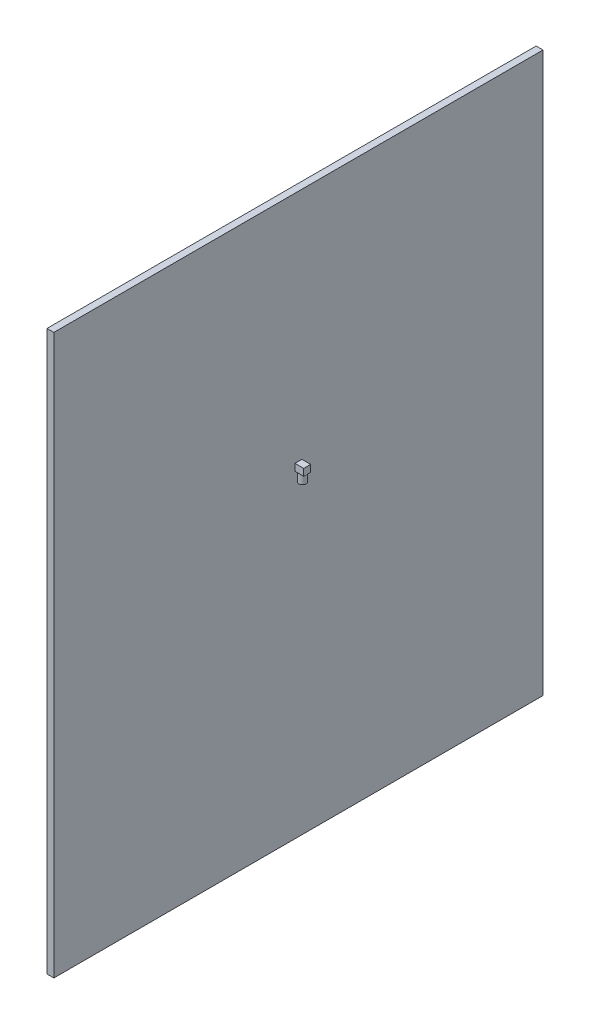
SolidWorks part; units mm, degrees
ref_plane "Front Plane" through (0, 0, 0) normal (0, 0, 1) x (1, 0, 0)
ref_plane "Top Plane" through (0, 0, 0) normal (0, 1, 0) x (1, 0, 0)
ref_plane "Right Plane" through (0, 0, 0) normal (1, 0, 0) x (0, 0, -1)
sketch "Sketch1" plane through (0, 0, 0) normal (1, 0, 0) x (0, 0, -1)
  line L1 (-355.6, 406.4) -> (355.6, 406.4)
  line L2 (-355.6, 406.4) -> (-355.6, -406.4)
  line L3 (-355.6, -406.4) -> (355.6, -406.4)
  line L4 (355.6, 406.4) -> (355.6, -406.4)
  line L5 (-355.6, 406.4) -> (355.6, -406.4) construction
  line L6 (-355.6, -406.4) -> (355.6, 406.4) construction
  point P0 (0, 0)
  dimension "D1" = 812.8
  dimension "D2" = 711.2
extrude "Boss-Extrude1" add sketch "Sketch1" along normal blind 10
sketch "Sketch2" plane through (10, 0, 0) normal (1, 0, 0) x (0, 0, -1)
  line L0 (0, 5.5) -> (0, -5.5) construction
  line L1 (-5, 66.3) -> (5, 66.3)
  line L2 (-5, 66.3) -> (-5, 56.3)
  line L3 (-5, 56.3) -> (5, 56.3)
  line L4 (5, 66.3) -> (5, 56.3)
  line L5 (-5, 66.3) -> (5, 56.3) construction
  line L6 (-5, 56.3) -> (5, 66.3) construction
  line L7 (-355.6, -406.4) -> (355.6, -406.4) construction
  point P0 (0, 61.3)
  dimension "D1" = 10
  dimension "D2" = 10
  dimension "D3" = 462.7
extrude "Boss-Extrude2" add sketch "Sketch2" along normal blind 12.7
sketch "Sketch4" plane through (0, 56.3, 0) normal (0, -1, 0) x (1, 0, 0)
  line L0 (12.485, 0) -> (-12.485, 0) construction
  line L1 (10, 355.6) -> (10, -355.6) construction
  circle A0 centre (16, 0) radius 5.335
  dimension "D1" = 10.67
  dimension "D2" = 6
extrude "Boss-Extrude5" add sketch "Sketch4" along normal blind 12.7
